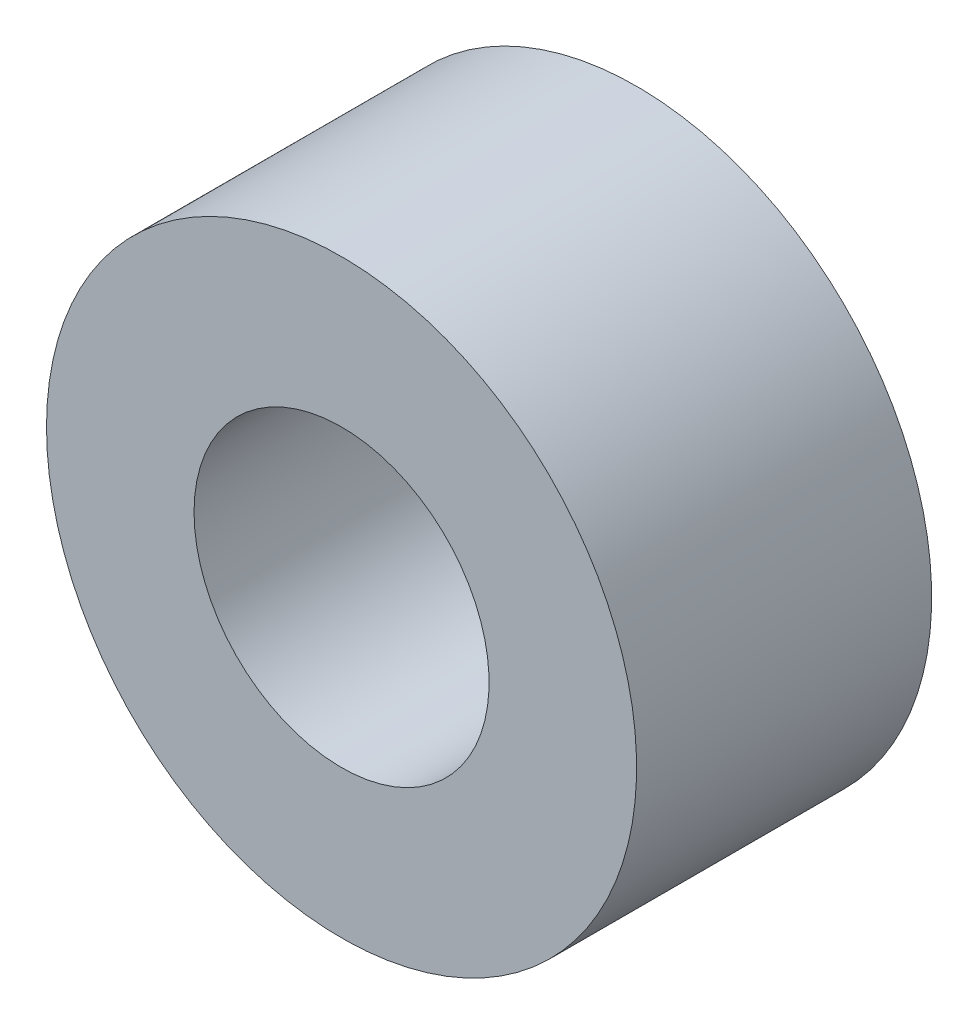
SolidWorks part; units mm, degrees
ref_plane "Front Plane" through (0, 0, 0) normal (0, 0, 1) x (1, 0, 0)
ref_plane "Top Plane" through (0, 0, 0) normal (0, 1, 0) x (1, 0, 0)
ref_plane "Right Plane" through (0, 0, 0) normal (1, 0, 0) x (0, 0, -1)
sketch "Sketch2" plane through (0, 0, 0) normal (1, 0, 0) x (0, 0, -1)
  line L0 (0, 0) -> (-41.003, 0) construction
  line L1 (-2.5, 5) -> (2.5, 5)
  line L2 (-2.5, 5) -> (-2.5, 2.5)
  line L3 (-2.5, 2.5) -> (2.5, 2.5)
  line L4 (2.5, 5) -> (2.5, 2.5)
  line L5 (-2.5, 5) -> (2.5, 2.5) construction
  line L6 (-2.5, 2.5) -> (2.5, 5) construction
  point P0 (0, 3.75)
  dimension "D1" = 10
  dimension "D2" = 5
  dimension "D3" = 5
revolve "Revolve1" add sketch "Sketch2" angle 360 about L0
sketch "Interface" plane through (0, 0, 0) normal (0, 0, 1) x (1, 0, 0)
  circle A0 centre (0, 0) radius 5
  circle A1 centre (0, 0) radius 2.5
  dimension "D1" = 10
  dimension "D2" = 5
sketch "Axis" plane through (0, 0, 0) normal (1, 0, 0) x (0, 0, -1)
  line L0 (2.5, 0) -> (-2.5, 0)
  point P3 (0, 0)
  dimension "D1" = 5
equation "\"D1@Sketch2\"=\"Bearing OD\""
equation "\"Bearing OD\"= 10mm"
equation "\"Bearing ID\"= 5mm"
equation "\"Bearing Thickness\"= 5mm"
equation "\"D2@Sketch2\"=\"Bearing ID\""
equation "\"D3@Sketch2\"=\"Bearing Thickness\""
equation "\"D1@Interface\" = \"Bearing OD\""
equation "\"D2@Interface\"=\"Bearing ID\""
equation "\"D1@Axis\" = \"Bearing Thickness\""
